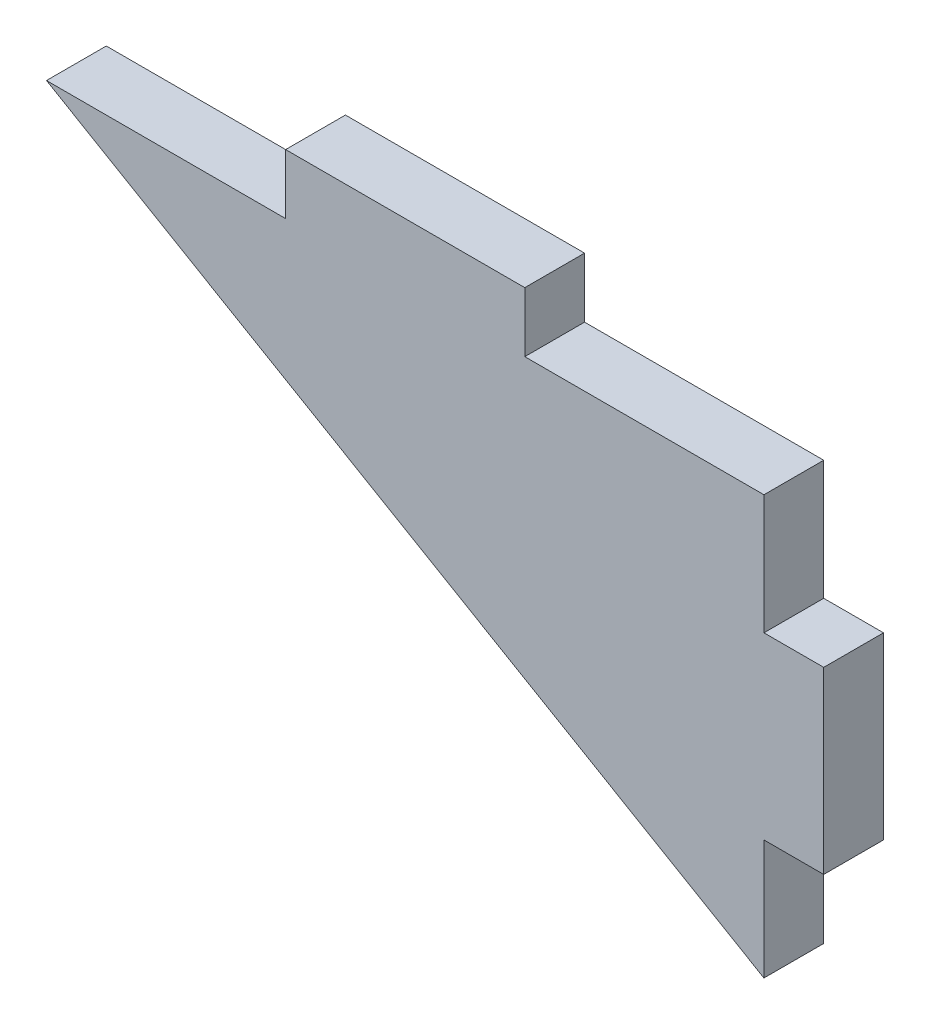
SolidWorks part; units mm, degrees
ref_plane "前视基准面" through (0, 0, 0) normal (0, 0, 1) x (1, 0, 0)
ref_plane "上视基准面" through (0, 0, 0) normal (0, 1, 0) x (1, 0, 0)
ref_plane "右视基准面" through (0, 0, 0) normal (1, 0, 0) x (0, 0, -1)
sketch "草图1" plane through (0, 0, 0) normal (0, 0, 1) x (1, 0, 0)
  line L0 (0, 0) -> (0, 10)
  line L1 (0, 10) -> (5, 10)
  line L2 (5, 10) -> (5, 25)
  line L3 (5, 25) -> (0, 25)
  line L4 (0, 25) -> (0, 35)
  line L5 (0, 35) -> (-20, 35)
  line L6 (-20, 35) -> (-20, 40)
  line L7 (-20, 40) -> (-40, 40)
  line L8 (-40, 40) -> (-40, 35)
  line L9 (-40, 35) -> (-60, 35)
  line L10 (-60, 35) -> (0, 0)
  dimension "D1" = 5
  dimension "D2" = 20
  dimension "D3" = 20
  dimension "D4" = 20
  dimension "D5" = 10
  dimension "D6" = 15
  dimension "D7" = 5
  dimension "D8" = 10
extrude "凸台-拉伸1" add sketch "草图1" along normal blind 5
